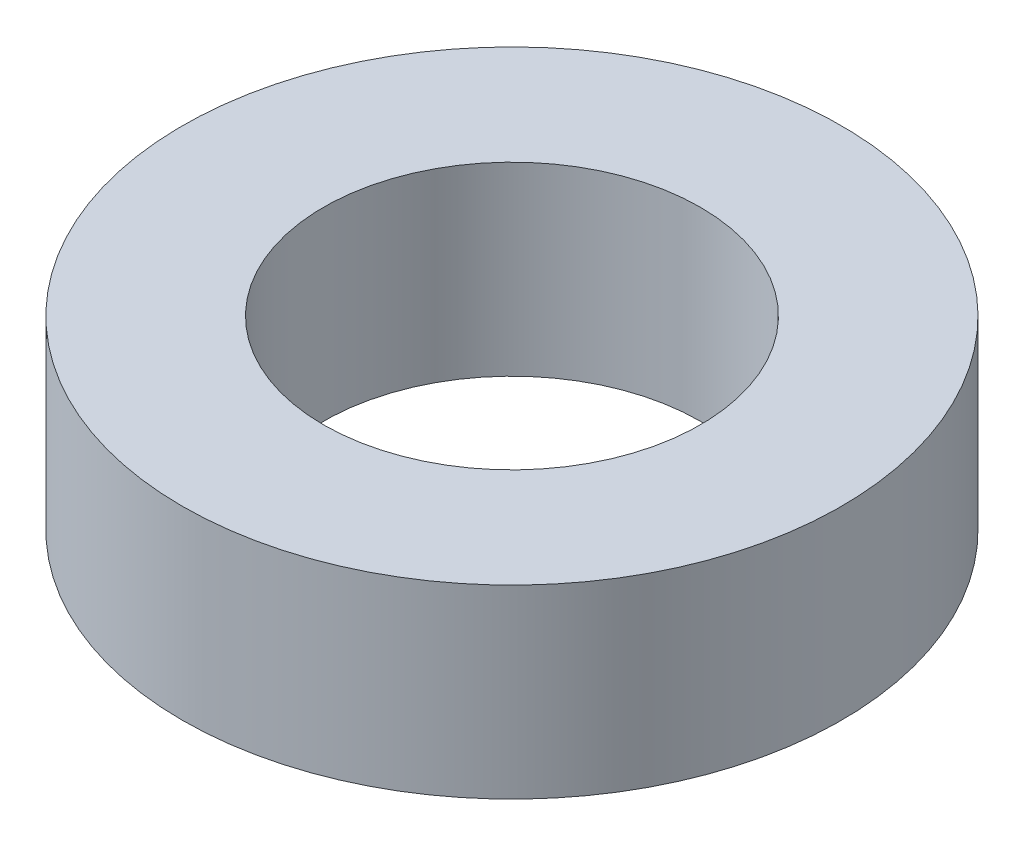
SolidWorks part; units mm, degrees
ref_plane "Front" through (0, 0, 0) normal (0, 0, 1) x (1, 0, 0)
ref_plane "Top" through (0, 0, 0) normal (0, 1, 0) x (1, 0, 0)
ref_plane "Right" through (0, 0, 0) normal (1, 0, 0) x (0, 0, -1)
sketch "Sketch1" plane through (0, 0, 0) normal (0, 1, 0) x (1, 0, 0)
  circle A0 centre (0, 0) radius 5.334
  circle A1 centre (0, 0) radius 3.05
  dimension "D1" = 10.668
  dimension "D2" = 6.1
extrude "Boss-Extrude1" add sketch "Sketch1" along normal blind 3
